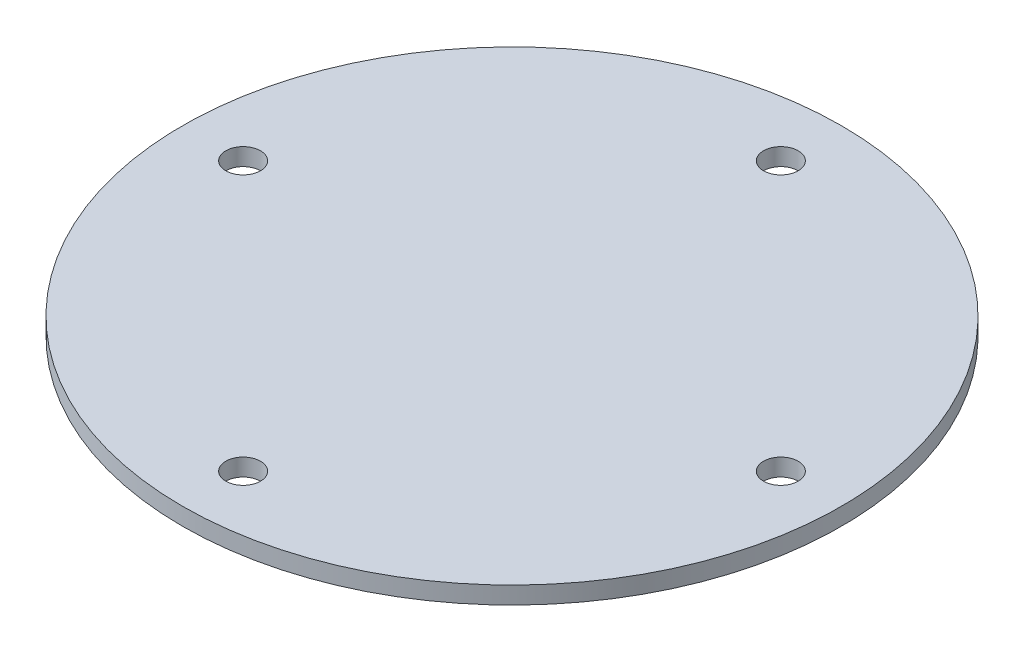
SolidWorks part; units mm, degrees
ref_plane "Front Plane" through (0, 0, 0) normal (0, 0, 1) x (1, 0, 0)
ref_plane "Top Plane" through (0, 0, 0) normal (0, 1, 0) x (1, 0, 0)
ref_plane "Right Plane" through (0, 0, 0) normal (1, 0, 0) x (0, 0, -1)
sketch "Sketch1" plane through (0, 0, 0) normal (0, 1, 0) x (1, 0, 0)
  circle A0 centre (0, 0) radius 23.5
  circle A1 centre (0, 0) radius 33
extrude "Boss-Extrude1" add sketch "Sketch1" against normal blind 8 contours A0
sketch "Sketch2" plane through (0, 0, 0) normal (0, 1, 0) x (1, 0, 0)
  circle A0 centre (0, 0) radius 38
extrude "Boss-Extrude2" add sketch "Sketch2" against normal blind 2
sketch "Sketch3" plane through (0, 0, 0) normal (0, 1, 0) x (1, 0, 0)
  circle A0 centre (0, 0) radius 15
extrude "Cut-Extrude1" cut sketch "Sketch3" against normal through all from offset 2 contours A0 offset against normal yes
sketch "Sketch4" plane through (0, 0, 0) normal (0, 1, 0) x (1, 0, 0)
  circle A0 centre (0, 31) radius 2
  circle A1 centre (31, 0) radius 2
  circle A2 centre (0, -31) radius 2
  circle A3 centre (-31, 0) radius 2
  point P11 (0, 0)
  dimension "D1" = 4
  dimension "D2" = 31
extrude "Cut-Extrude2" cut sketch "Sketch4" against normal through all
